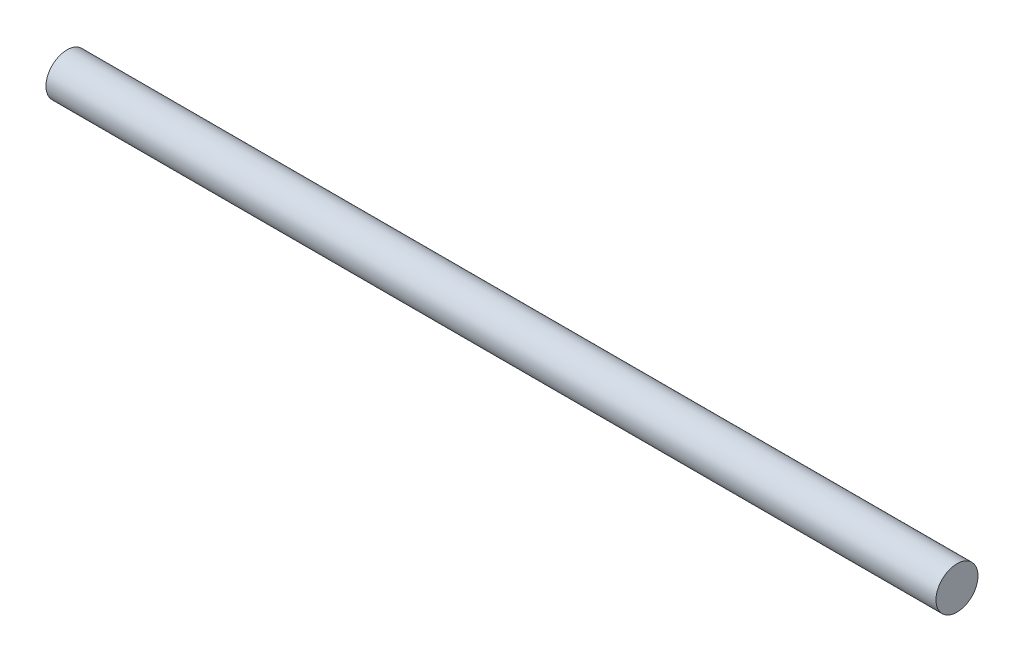
SolidWorks part; units mm, degrees
material "Copper"
ref_plane "Front Plane" through (0, 0, 0) normal (0, 0, 1) x (1, 0, 0)
ref_plane "Top Plane" through (0, 0, 0) normal (0, 1, 0) x (1, 0, 0)
ref_plane "Right Plane" through (0, 0, 0) normal (1, 0, 0) x (0, 0, -1)
sketch "Sketch1" plane through (0, 0, 0) normal (1, 0, 0) x (0, 0, -1)
  circle A0 centre (0, 0) radius 0.2921
  dimension "D1" = 0.5842
extrude "Boss-Extrude1" add sketch "Sketch1" along normal blind 12.37
